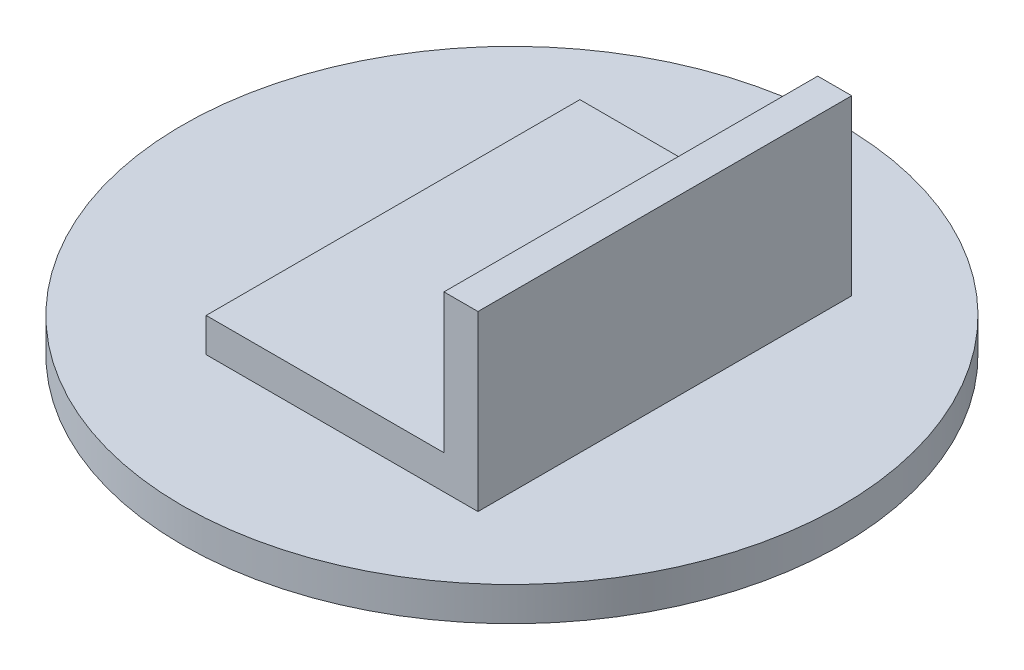
SolidWorks part; units mm, degrees
ref_plane "Front Plane" through (0, 0, 0) normal (0, 0, 1) x (1, 0, 0)
ref_plane "Top Plane" through (0, 0, 0) normal (0, 1, 0) x (1, 0, 0)
ref_plane "Right Plane" through (0, 0, 0) normal (1, 0, 0) x (0, 0, -1)
sketch "Sketch2" plane through (0, 0, 0) normal (0, 1, 0) x (1, 0, 0)
  circle A0 centre (0, 0) radius 48.5
  dimension "D1" = 97
extrude "Boss-Extrude1" add sketch "Sketch2" along normal blind 5
sketch "Sketch6" plane through (0, 5, 0) normal (0, 1, 0) x (1, 0, 0)
  line L1 (17.5, 27.5) -> (-17.5, 27.5)
  line L2 (17.5, 27.5) -> (17.5, -27.5)
  line L3 (17.5, -27.5) -> (-17.5, -27.5)
  line L4 (-17.5, 27.5) -> (-17.5, -27.5)
  line L5 (17.5, 27.5) -> (-17.5, -27.5) construction
  line L6 (17.5, -27.5) -> (-17.5, 27.5) construction
  point P0 (0, 0)
  dimension "D1" = 35
  dimension "D2" = 55
extrude "Boss-Extrude2" add sketch "Sketch6" along normal blind 5
sketch "Sketch4" plane through (0, 0, 0) normal (0, -1, 0) x (1, 0, 0)
  circle A0 centre (0, 7.25) radius 1.5
  circle A1 centre (0, -7.25) radius 1.5
  dimension "D1" = 3
  dimension "D2" = 3
  dimension "D3" = 14.5
  dimension "D4" = 7.25
extrude "Cut-Extrude2" cut sketch "Sketch4" against normal through all
sketch "Sketch5" plane through (0, 0, 0) normal (0, -1, 0) x (1, 0, 0)
  circle A0 centre (0, 0) radius 3.75
  dimension "D1" = 7.5
extrude "Cut-Extrude3" cut sketch "Sketch5" against normal blind 1.5
sketch "Sketch7" plane through (0, 5, 0) normal (0, 1, 0) x (1, 0, 0)
  line L1 (17.5, 27.5) -> (22.5, 27.5)
  line L2 (17.5, 27.5) -> (17.5, -27.5)
  line L3 (17.5, -27.5) -> (22.5, -27.5)
  line L4 (22.5, 27.5) -> (22.5, -27.5)
  dimension "D1" = 5
extrude "Boss-Extrude3" add sketch "Sketch7" along normal blind 25.5
